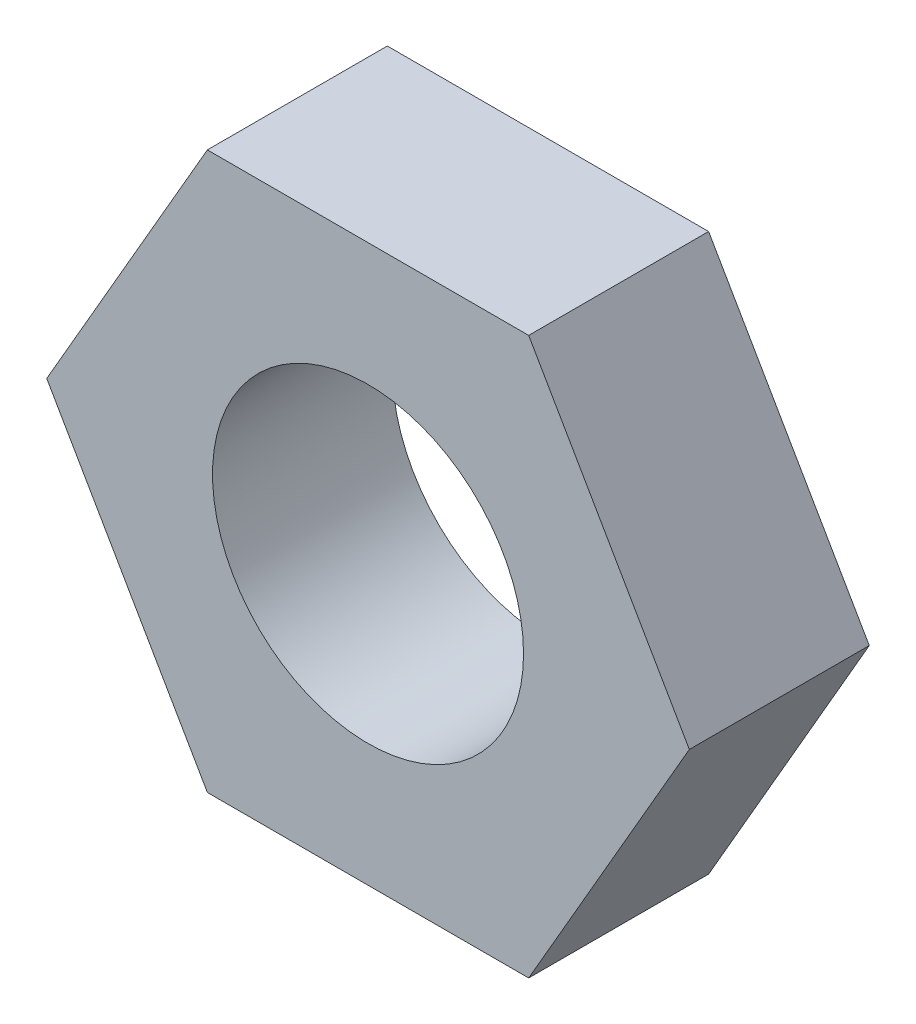
SolidWorks part; units mm, degrees
ref_plane "Front Plane" through (0, 0, 0) normal (0, 0, 1) x (1, 0, 0)
ref_plane "Top Plane" through (0, 0, 0) normal (0, 1, 0) x (1, 0, 0)
ref_plane "Right Plane" through (0, 0, 0) normal (1, 0, 0) x (0, 0, -1)
sketch "Sketch2" plane through (0, 0, 0) normal (0, 0, 1) x (1, 0, 0)
  line L1 (12.5, 0) -> (6.25, 10.8253)
  line L2 (6.25, 10.8253) -> (-6.25, 10.8253)
  line L3 (-6.25, 10.8253) -> (-12.5, 0)
  line L4 (-12.5, 0) -> (-6.25, -10.8253)
  line L5 (-6.25, -10.8253) -> (6.25, -10.8253)
  line L6 (6.25, -10.8253) -> (12.5, 0)
  circle A1 centre (0, 0) radius 6.05
  dimension "D2" = 12.1
  dimension "D1" = 25
extrude "Boss-Extrude1" add sketch "Sketch2" along normal blind 7
